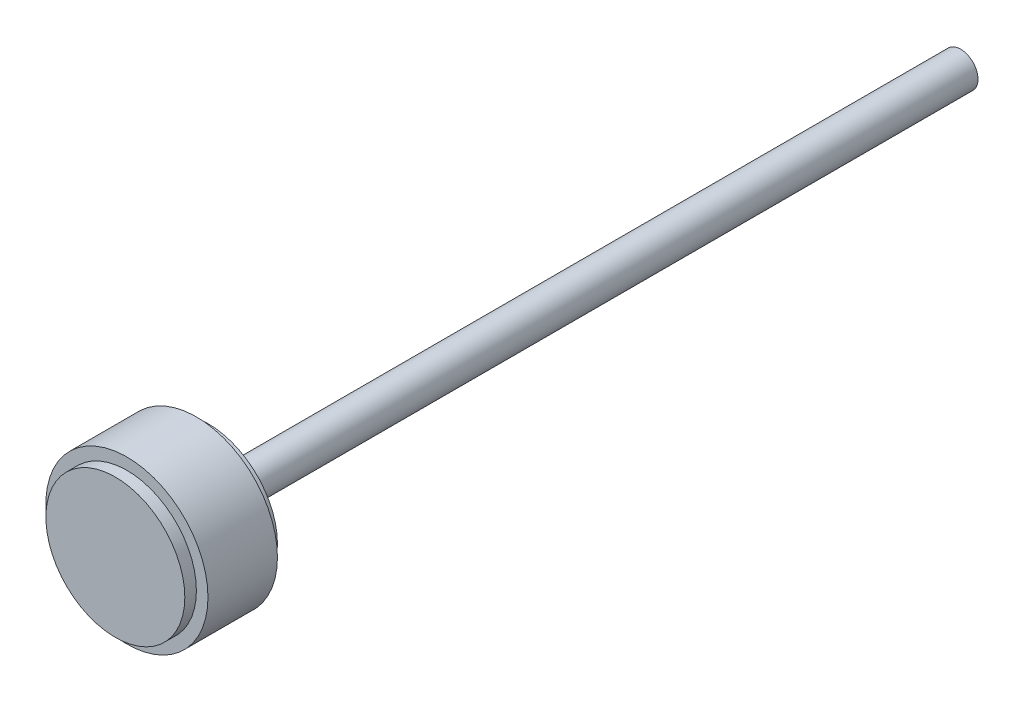
SolidWorks part; units mm, degrees
ref_plane "Front Plane" through (0, 0, 0) normal (0, 0, 1) x (1, 0, 0)
ref_plane "Top Plane" through (0, 0, 0) normal (0, 1, 0) x (1, 0, 0)
ref_plane "Right Plane" through (0, 0, 0) normal (1, 0, 0) x (0, 0, -1)
sketch "Sketch1" plane through (0, 0, 0) normal (0, 0, 1) x (1, 0, 0)
  circle A0 centre (0, 0) radius 7.5
  dimension "D1" = 15
extrude "Boss-Extrude1" add sketch "Sketch1" against normal blind 320
sketch "Sketch2" plane through (0, 0, 0) normal (0, 0, 1) x (1, 0, 0)
  circle A0 centre (0, 0) radius 10
  dimension "D1" = 20
extrude "Boss-Extrude2" add sketch "Sketch2" along normal blind 5
sketch "Sketch3" plane through (0, 0, 5) normal (0, 0, 1) x (1, 0, 0)
  circle A0 centre (0, 0) radius 30
  dimension "D1" = 60
extrude "Boss-Extrude3" add sketch "Sketch3" along normal blind 5
sketch "Sketch4" plane through (0, 0, 10) normal (0, 0, 1) x (1, 0, 0)
  circle A0 centre (0, 0) radius 35
  circle A1 centre (0, 0) radius 30
  circle A2 centre (0, 0) radius 30
  circle M2 centre (0, 0) radius 30
  dimension "D1" = 0
  dimension "D2" = 5
extrude "Boss-Extrude4" add sketch "Sketch4" along normal blind 30 contours M2 | A0 M2
sketch "Sketch5" plane through (0, 0, 40) normal (0, 0, 1) x (1, 0, 0)
  circle A0 centre (0, 0) radius 30
  circle A1 centre (0, 0) radius 35
  circle A2 centre (0, 0) radius 35
  dimension "D1" = 0
  dimension "D2" = 5
extrude "Boss-Extrude5" add sketch "Sketch5" along normal blind 5 contours A0
